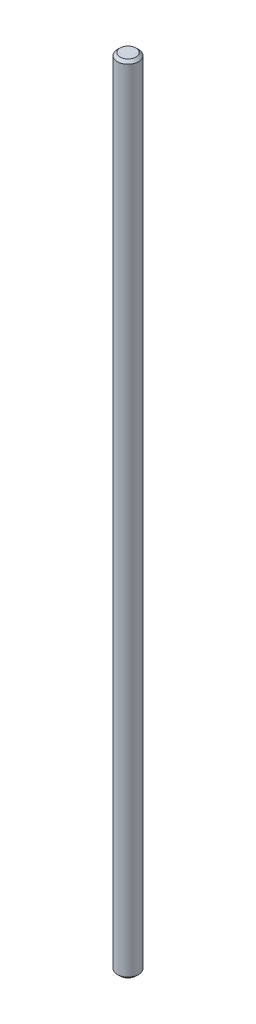
SolidWorks part; units mm, degrees
ref_plane "前视基准面" through (0, 0, 0) normal (0, 0, 1) x (1, 0, 0)
ref_plane "上视基准面" through (0, 0, 0) normal (0, 1, 0) x (1, 0, 0)
ref_plane "右视基准面" through (0, 0, 0) normal (1, 0, 0) x (0, 0, -1)
sketch "草图1" plane through (0, 0, 0) normal (0, 1, 0) x (1, 0, 0)
  circle A0 centre (0, 0) radius 4
  dimension "D1" = 8
extrude "凸台-拉伸1" add sketch "草图1" along normal blind 300
cosmetic thread "装饰螺纹线1" parameters "D2"=6.647
chamfer "倒角1" distance 1 angle 45 2 edges at (0, 0, 4) (0, 300, 4)
